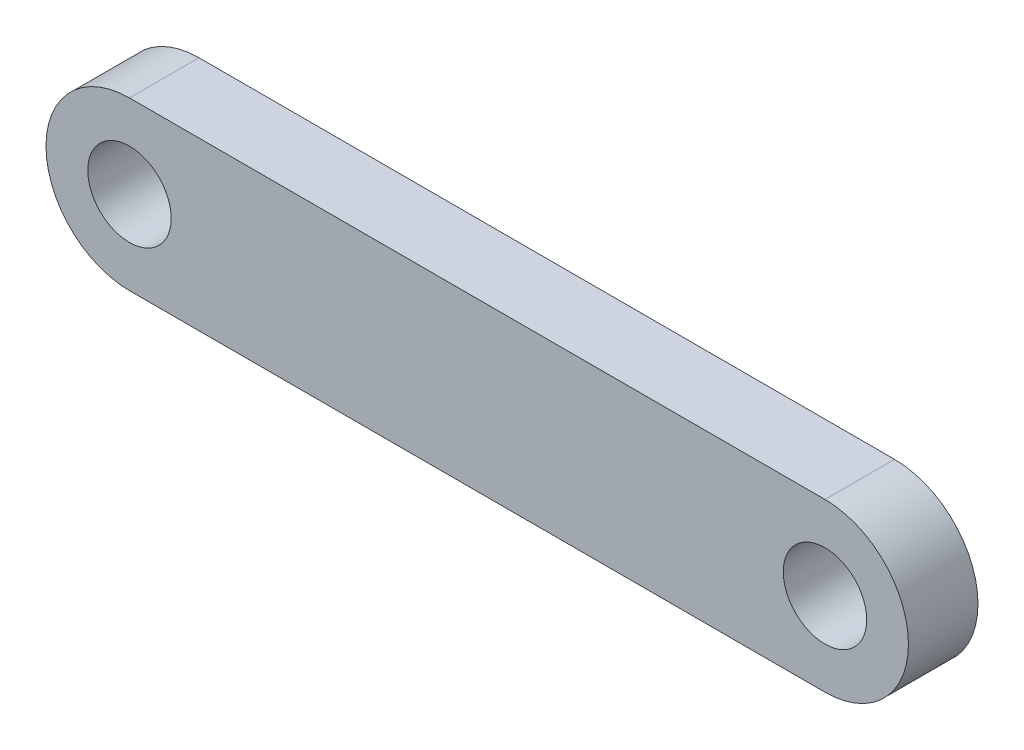
SolidWorks part; units mm, degrees
ref_plane "Front Plane" through (0, 0, 0) normal (0, 0, 1) x (1, 0, 0)
ref_plane "Top Plane" through (0, 0, 0) normal (0, 1, 0) x (1, 0, 0)
ref_plane "Right Plane" through (0, 0, 0) normal (1, 0, 0) x (0, 0, -1)
sketch "Sketch1" plane through (0, 0, 0) normal (0, 0, 1) x (1, 0, 0)
  line L0 (-25, 0) -> (25, 0) construction
  line L1 (-25, 6) -> (25, 6)
  line L2 (-25, -6) -> (25, -6)
  arc A0 (-25, 6) -> (-25, -6) centre (-25, 0) ccw
  arc A1 (25, -6) -> (25, 6) centre (25, 0) ccw
  circle A2 centre (-25, 0) radius 3
  circle A3 centre (25, 0) radius 3
  point P2 (0, 0)
  dimension "D2" = 6
  dimension "D3" = 6
  dimension "D4" = 6
  dimension "D1" = 50
extrude "Boss-Extrude1" add sketch "Sketch1" along normal mid plane 5
